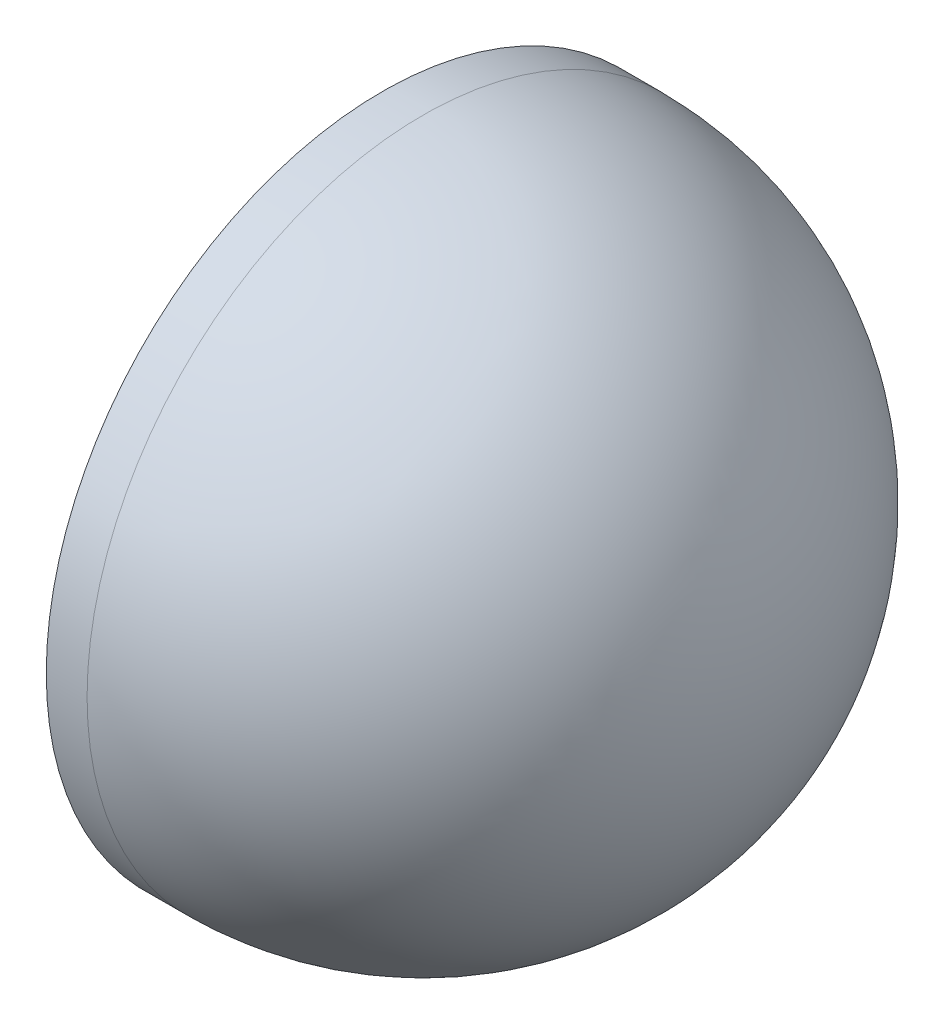
SolidWorks part; units mm, degrees
ref_plane "Front Plane" through (0, 0, 0) normal (0, 0, 1) x (1, 0, 0)
ref_plane "Top Plane" through (0, 0, 0) normal (0, 1, 0) x (1, 0, 0)
ref_plane "Right Plane" through (0, 0, 0) normal (1, 0, 0) x (0, 0, -1)
sketch "Sketch1" plane through (0, 0, 0) normal (0, 0, 1) x (1, 0, 0)
  line L0 (0, 0) -> (1996.8504, 0) construction
  line L1 (776, 0) -> (823, 0)
  line L3 (0, -776) -> (-100, -776)
  line L5 (0, -823) -> (-100, -823)
  line L6 (-100, -776) -> (-100, -823)
  arc A0 (776, 0) -> (0, -776) centre (0, 0) cw
  arc A1 (823, 0) -> (0, -823) centre (0, 0) cw
  point P11 (0, 0)
  point P12 (0, 0)
  point P13 (0, 0)
  dimension "D1" = 776
  dimension "D2" = 823
  dimension "D3" = 100
revolve "Revolve1" add sketch "Sketch1" angle 360 about L0
